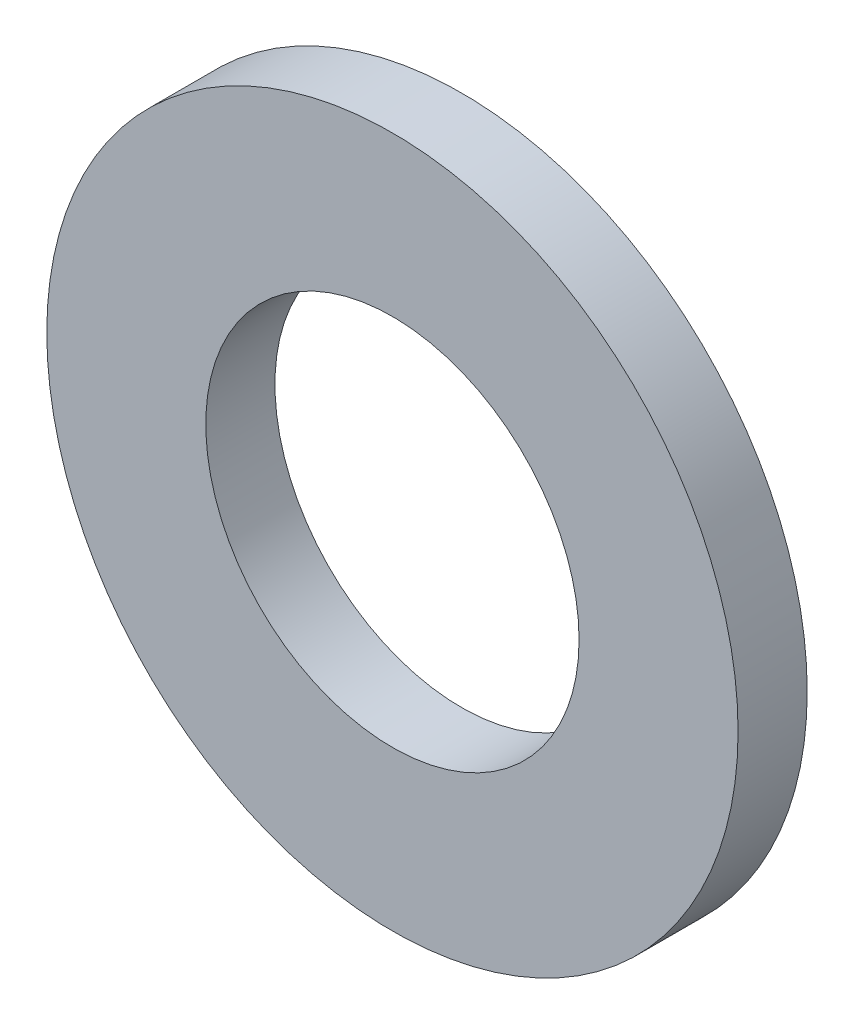
SolidWorks part; units mm, degrees
ref_plane "Front Plane" through (0, 0, 0) normal (0, 0, 1) x (1, 0, 0)
ref_plane "Top Plane" through (0, 0, 0) normal (0, 1, 0) x (1, 0, 0)
ref_plane "Right Plane" through (0, 0, 0) normal (1, 0, 0) x (0, 0, -1)
other "Configuration Table"
sketch "Sketch2" plane through (0, 0, 0) normal (0, 0, 1) x (1, 0, 0)
  circle A0 centre (0, 0) radius 5
extrude "Clearance_washer" add sketch "Sketch2" along normal blind 1 from offset 0
sketch "Sketch3" plane through (0, 0, 0) normal (0, 0, 1) x (1, 0, 0)
  circle A0 centre (0, 0) radius 2.7
extrude "Clearance_washer_bore" cut sketch "Sketch3" along normal blind 1 from offset 0
